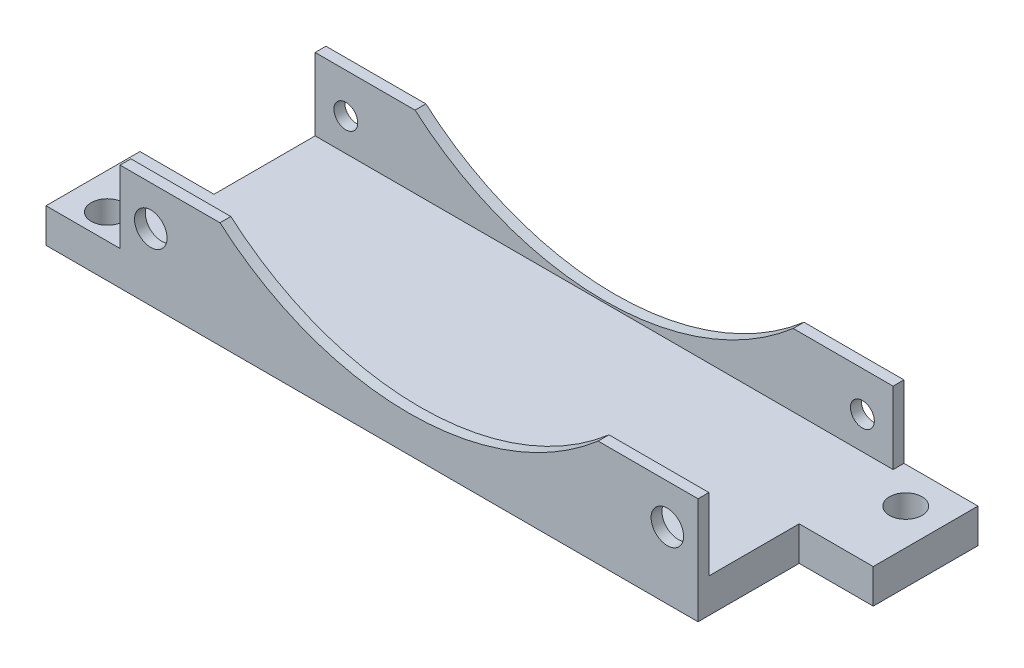
SolidWorks part; units mm, degrees
ref_plane "Front Plane" through (0, 0, 0) normal (0, 0, 1) x (1, 0, 0)
ref_plane "Top Plane" through (0, 0, 0) normal (0, 1, 0) x (1, 0, 0)
ref_plane "Right Plane" through (0, 0, 0) normal (1, 0, 0) x (0, 0, -1)
sketch "Sketch1" plane through (0, 0, 0) normal (0, 0, 1) x (1, 0, 0)
  line L0 (-35.75, 3.125) -> (35.75, 3.125)
  line L1 (-40, -7.375) -> (40, -7.375)
  line L2 (-40, -7.375) -> (-40, 7.375)
  line L3 (-40, 7.375) -> (40, 7.375)
  line L4 (40, -7.375) -> (40, 7.375)
  line L5 (-40, -7.375) -> (40, 7.375) construction
  line L6 (-40, 7.375) -> (40, -7.375) construction
  line L7 (-40, -2.625) -> (40, -2.625)
  point P0 (0, 0)
  point P8 (0, 3.125)
  point P10 (35.75, 3.125)
  dimension "D1" = 14.75
  dimension "D2" = 80
  dimension "D3" = 71.5
  dimension "D4" = 4.25
  dimension "D5" = 4.75
extrude "Boss-Extrude1" add sketch "Sketch1" along normal blind 28.5
sketch "Sketch7" plane through (-40, 0, 0) normal (-1, 0, 0) x (0, 0, 1)
  line L0 (28.5, -7.375) -> (0, -7.375) construction
  line L1 (1.5, -2.625) -> (27, -2.625)
  line L2 (1.5, -2.625) -> (1.5, 7.375)
  line L3 (1.5, 7.375) -> (27, 7.375)
  line L4 (27, -2.625) -> (27, 7.375)
  line L5 (1.5, -2.625) -> (27, 7.375) construction
  line L6 (1.5, 7.375) -> (27, -2.625) construction
  line L7 (28.5, 7.375) -> (0, 7.375) construction
  line L8 (0, -7.375) -> (0, 7.375) construction
  point P0 (14.25, 2.375)
  dimension "D1" = 25.5
  dimension "D2" = 4.75
  dimension "D3" = 14.25
extrude "Cut-Extrude3" cut sketch "Sketch7" against normal through all
hole_wizard "M4x0.7 Tapped Hole3" positions "Sketch9" profile "Sketch11" tap size "M4x0.7" standard "ANSI Metric"
sketch "Sketch9" plane through (0, 0, 1.5) normal (0, 0, 1) x (1, 0, 0)
  line L0 (-35.75, 1.875) -> (35.75, 1.875)
  line L1 (-40, -7.375) -> (40, -7.375) construction
  point P0 (-35.75, 1.875)
  point P1 (35.75, 1.875)
  point P4 (0, 1.875)
  dimension "D1" = 71.5
  dimension "D2" = 9.25
sketch "Sketch11" plane through (-35.75, 1.875, 1.5) normal (1, 0, 0) x (0, -1, 0)
  line L0 (0, 0) -> (0, 1.5)
  line L1 (0, 1.5) -> (1.65, 1.5)
  line L2 (1.65, 1.5) -> (1.65, 0)
  line L5 (1.65, 0) -> (0, 0)
  line L11 (0, -6.35) -> (0, 107.95) construction
  dimension "Thru Tap Drill Dia." = 3.3
  dimension "Thru Tap Drill Depth" = 1.5
cosmetic thread "Hole Thread5" parameters "D2"=4
cosmetic thread "Hole Thread6" parameters "D2"=4
hole_wizard "M4 Clearance Hole1" positions "Sketch12" profile "Sketch14" hole size "M4" standard "ANSI Metric"
sketch "Sketch12" plane through (0, 0, 27) normal (0, 0, -1) x (-1, 0, 0)
  point P0 (-35.75, 1.875)
  point P3 (35.75, 1.875)
sketch "Sketch14" plane through (35.75, 1.875, 27) normal (1, 0, 0) x (0, 1, 0)
  line L0 (0, 0) -> (0, 1.5)
  line L1 (0, 1.5) -> (2.25, 1.5)
  line L2 (2.25, 1.5) -> (2.25, 0)
  line L5 (2.25, 0) -> (0, 0)
  line L11 (0, -6.35) -> (0, 107.95) construction
  dimension "Thru Hole Dia." = 4.5
  dimension "Thru Hole Depth" = 1.5
sketch "Sketch15" plane through (0, 0, 28.5) normal (0, 0, 1) x (1, 0, 0)
  line L0 (-40, -7.375) -> (40, -7.375) construction
  circle A0 centre (0, 37.625) radius 40
  dimension "D1" = 80
  dimension "D2" = 45
extrude "Cut-Extrude4" cut sketch "Sketch15" against normal through all
sketch "Sketch19" plane through (0, -7.375, 0) normal (0, -1, 0) x (1, 0, 0)
  line L1 (-40, 28.5) -> (-50.25, 28.5)
  line L2 (-40, 28.5) -> (-40, 15.5)
  line L3 (-40, 15.5) -> (-50.25, 15.5)
  line L4 (-50.25, 28.5) -> (-50.25, 15.5)
  line L5 (40, 0) -> (50.25, 0)
  line L6 (40, 0) -> (40, 14.5)
  line L7 (40, 14.5) -> (50.25, 14.5)
  line L8 (50.25, 0) -> (50.25, 14.5)
  dimension "D1" = 10.25
  dimension "D2" = 13
  dimension "D3" = 10.25
  dimension "D4" = 14.5
extrude "Boss-Extrude3" add sketch "Sketch19" against normal up to vertex
hole_wizard "M4 Clearance Hole3" positions "Sketch20" profile "Sketch21" hole size "M4" standard "ANSI Metric" end condition through all
sketch "Sketch20" plane through (0, -2.625, 0) normal (0, 1, 0) x (1, 0, 0)
  line L0 (-50.25, -28.5) -> (-50.25, -15.5) construction
  line L1 (-40, -28.5) -> (-50.25, -28.5) construction
  line L2 (50.25, 0) -> (50.25, -14.5) construction
  point P0 (-45.25, -25)
  point P7 (45.25, -5)
  point P10 (0, 0)
  dimension "D1" = 5
  dimension "D2" = 3.5
  dimension "D3" = 5
  dimension "D4" = 5
sketch "Sketch21" plane through (-45.25, -2.625, 25) normal (1, 0, 0) x (0, 0, 1)
  line L0 (0, 0) -> (0, 4.75)
  line L1 (0, 4.75) -> (2.25, 4.75)
  line L2 (2.25, 4.75) -> (2.25, 0)
  line L5 (2.25, 0) -> (0, 0)
  line L11 (0, -6.35) -> (0, 107.95) construction
  dimension "Thru Hole Dia." = 4.5
  dimension "Thru Hole Depth" = 4.75
hole_wizard "M4x0.7 Tapped Hole4" [suppressed] positions "Sketch22" profile "Sketch24" tap size "M4x0.7" standard "ANSI Metric"
sketch "Sketch22" plane through (0, -2.625, 0) normal (0, 1, 0) x (1, 0, 0)
  line L0 (-25, -14.25) -> (25, -14.25)
  line L2 (-26.1713, -1.5) -> (-40, -1.5) construction
  point P1 (-25, -14.25)
  point P2 (25, -14.25)
  point P5 (0, -14.25)
  dimension "D1" = 50
  dimension "D2" = 12.75
sketch "Sketch24" plane through (-25, -2.625, 14.25) normal (1, 0, 0) x (0, 0, 1)
  line L0 (0, 0) -> (0, 4.75)
  line L1 (0, 4.75) -> (1.65, 4.75)
  line L2 (1.65, 4.75) -> (1.65, 0)
  line L5 (1.65, 0) -> (0, 0)
  line L11 (0, -6.35) -> (0, 107.95) construction
  dimension "Thru Tap Drill Dia." = 3.3
  dimension "Thru Tap Drill Depth" = 4.75
cosmetic thread "Hole Thread7" [suppressed] parameters "D2"=4
cosmetic thread "Hole Thread8" [suppressed] parameters "D2"=4
sketch "Sketch25" [suppressed] plane through (0, -2.625, 0) normal (0, 1, 0) x (1, 0, 0)
  circle A0 centre (-25, -14.25) radius 5
  circle A1 centre (25, -14.25) radius 5
  dimension "D1" = 10
  dimension "D2" = 10
extrude "Cut-Extrude5" [suppressed] cut sketch "Sketch25" against normal blind 2.5
